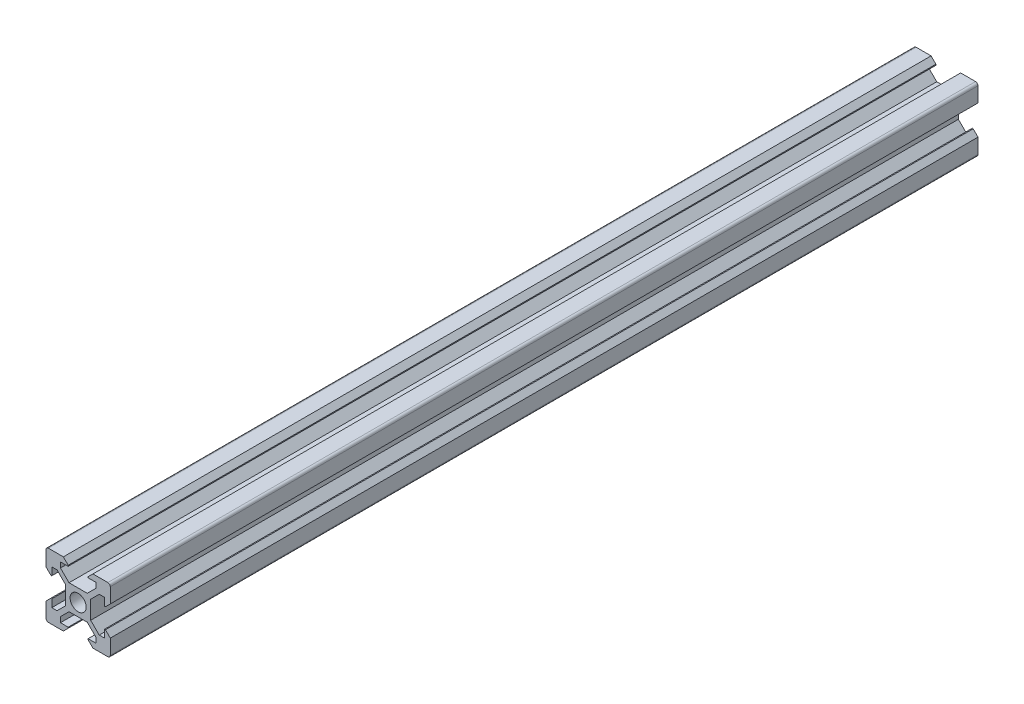
SolidWorks part; units mm, degrees
other "Markup1"
sketch "Sketch1" plane through (10, 10, 480) normal (0.5774, 0.5773, 0.5774) x (0.7071, 0, -0.7071)
ref_plane "Alzado" through (0, 0, 0) normal (0, 0, 1) x (1, 0, 0)
ref_plane "Planta" through (0, 0, 0) normal (0, 1, 0) x (1, 0, 0)
ref_plane "Vista lateral" through (0, 0, 0) normal (1, 0, 0) x (0, 0, -1)
sketch "Croquis1" plane through (0, 0, 0) normal (0, 0, 1) x (1, 0, 0)
  line L0 (-4.6, 10) -> (-3.1, 8.5)
  line L3 (-4.6, 10) -> (-9.25, 10)
  line L5 (-3.1, 8.5) -> (-3.1, 8.2)
  line L6 (-3.1, 8.2) -> (-5.5, 8.2)
  line L7 (-5.5, 8.2) -> (-5.5, 6.5607)
  line L8 (-5.5, 6.5607) -> (-2.84, 3.9007)
  line L9 (-2.84, 3.9007) -> (0, 3.9007)
  line L10 (0, 0) -> (-15.3499, 15.3499) construction
  line L11 (-3.9007, 2.84) -> (-3.9007, 0)
  line L12 (-6.5607, 5.5) -> (-3.9007, 2.84)
  line L13 (-8.2, 5.5) -> (-6.5607, 5.5)
  line L14 (-8.2, 3.1) -> (-8.2, 5.5)
  line L15 (-8.5, 3.1) -> (-8.2, 3.1)
  line L16 (-10, 4.6) -> (-10, 9.25)
  line L17 (-10, 4.6) -> (-8.5, 3.1)
  line L18 (10, 4.6) -> (8.5, 3.1)
  line L19 (10, 4.6) -> (10, 9.25)
  line L20 (8.5, 3.1) -> (8.2, 3.1)
  line L21 (8.2, 3.1) -> (8.2, 5.5)
  line L22 (8.2, 5.5) -> (6.5607, 5.5)
  line L23 (6.5607, 5.5) -> (3.9007, 2.84)
  line L24 (3.9007, 2.84) -> (3.9007, 0)
  line L25 (5.5, 6.5607) -> (2.84, 3.9007)
  line L26 (5.5, 8.2) -> (5.5, 6.5607)
  line L27 (3.1, 8.2) -> (5.5, 8.2)
  line L28 (3.1, 8.5) -> (3.1, 8.2)
  line L29 (4.6, 10) -> (9.25, 10)
  line L30 (4.6, 10) -> (3.1, 8.5)
  line L31 (2.84, 3.9007) -> (0, 3.9007)
  line L32 (4.6, -10) -> (3.1, -8.5)
  line L33 (4.6, -10) -> (9.25, -10)
  line L34 (3.1, -8.5) -> (3.1, -8.2)
  line L35 (3.1, -8.2) -> (5.5, -8.2)
  line L36 (5.5, -8.2) -> (5.5, -6.5607)
  line L37 (5.5, -6.5607) -> (2.84, -3.9007)
  line L38 (2.84, -3.9007) -> (0, -3.9007)
  line L39 (6.5607, -5.5) -> (3.9007, -2.84)
  line L40 (8.2, -5.5) -> (6.5607, -5.5)
  line L41 (8.2, -3.1) -> (8.2, -5.5)
  line L42 (8.5, -3.1) -> (8.2, -3.1)
  line L43 (10, -4.6) -> (10, -9.25)
  line L44 (10, -4.6) -> (8.5, -3.1)
  line L45 (3.9007, -2.84) -> (3.9007, 0)
  line L46 (-10, -4.6) -> (-8.5, -3.1)
  line L47 (-10, -4.6) -> (-10, -9.25)
  line L48 (-8.5, -3.1) -> (-8.2, -3.1)
  line L49 (-8.2, -3.1) -> (-8.2, -5.5)
  line L50 (-8.2, -5.5) -> (-6.5607, -5.5)
  line L51 (-6.5607, -5.5) -> (-3.9007, -2.84)
  line L52 (-3.9007, -2.84) -> (-3.9007, 0)
  line L53 (-5.5, -6.5607) -> (-2.84, -3.9007)
  line L54 (-5.5, -8.2) -> (-5.5, -6.5607)
  line L55 (-3.1, -8.2) -> (-5.5, -8.2)
  line L56 (-3.1, -8.5) -> (-3.1, -8.2)
  line L57 (-4.6, -10) -> (-9.25, -10)
  line L58 (-4.6, -10) -> (-3.1, -8.5)
  line L59 (-2.84, -3.9007) -> (0, -3.9007)
  circle A0 centre (0, 0) radius 2.5
  arc A1 (-9.25, 10) -> (-10, 9.25) centre (-9.25, 9.25) ccw
  arc A2 (10, 9.25) -> (9.25, 10) centre (9.25, 9.25) ccw
  arc A3 (9.25, -10) -> (10, -9.25) centre (9.25, -9.25) ccw
  arc A4 (-10, -9.25) -> (-9.25, -10) centre (-9.25, -9.25) ccw
  point P18 (-10, 10)
  point P37 (10, 10)
  point P55 (10, -10)
  point P73 (-10, -10)
  point P79 (0, 0)
  dimension "D1" = 5
  dimension "D5" = 0.75
  dimension "D2" = 10
  dimension "D3" = 10
  dimension "D4" = 4.6
  dimension "D6" = 5.5
  dimension "D7" = 135
  dimension "D8" = 0.75
  dimension "D9" = 225
  dimension "D10" = 2.84
  dimension "D11" = 1.8
  dimension "D12" = 3.1
  dimension "D13" = 4
extrude "Saliente-Extruir1" add sketch "Croquis1" along normal blind 300
sketch "Sketch2" plane through (0, 0, 0) normal (0, 1, 0) x (1, 0, 0)
  line L0 (-4.6, 0) -> (-9.25, 0) construction
  line L1 (-57.4359, -270) -> (82.1467, -270)
  line L2 (-57.4359, -270) -> (-57.4359, -512.4329)
  line L3 (-57.4359, -512.4329) -> (82.1467, -512.4329)
  line L4 (82.1467, -270) -> (82.1467, -512.4329)
  dimension "D1" = 270
extrude "Cut-Extrude1" cut sketch "Sketch2" against normal blind 40 and the other way blind 47
